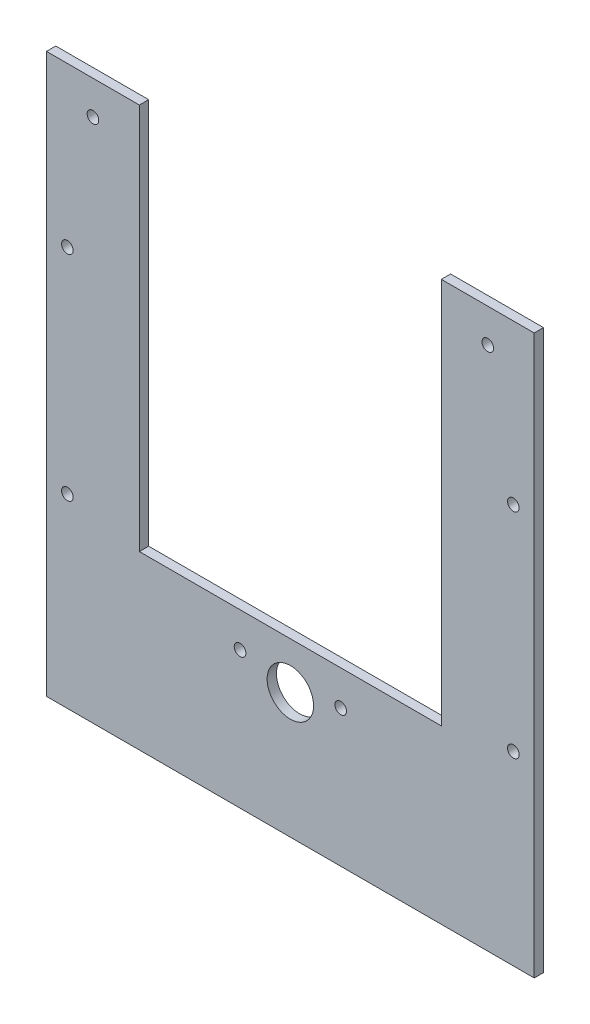
SolidWorks part; units mm, degrees
ref_plane "Alzado" through (0, 0, 0) normal (0, 0, 1) x (1, 0, 0)
ref_plane "Planta" through (0, 0, 0) normal (0, 1, 0) x (1, 0, 0)
ref_plane "Vista lateral" through (0, 0, 0) normal (1, 0, 0) x (0, 0, -1)
sketch "Croquis1" plane through (0, 0, 0) normal (0, 0, 1) x (1, 0, 0)
  line L0 (-79.4984, 944.1284) -> (-79.4984, 777.6284)
  line L1 (90.5016, 703.6284) -> (-119.4984, 703.6284)
  line L2 (90.5016, 703.6284) -> (90.5016, 944.1284)
  line L3 (90.5016, 944.1284) -> (50.5016, 944.1284)
  line L4 (-119.4984, 703.6284) -> (-119.4984, 944.1284)
  line L5 (-79.4984, 777.6284) -> (50.5016, 777.6284)
  line L6 (50.5016, 777.6284) -> (50.5016, 944.1284)
  line L7 (-79.4984, 944.1284) -> (-119.4984, 944.1284)
  circle A0 centre (70.5016, 929.6284) radius 2.5
  circle A1 centre (81.5016, 875.6184) radius 2.5
  circle A2 centre (81.5016, 783.6184) radius 2.5
  circle A3 centre (-36.1651, 762.6284) radius 2.5
  circle A4 centre (-110.4984, 783.6184) radius 2.5
  circle A5 centre (-110.4984, 875.6184) radius 2.5
  circle A6 centre (-99.4984, 929.6284) radius 2.5
  circle A7 centre (7.1683, 762.6284) radius 2.5
  circle A8 centre (-14.4984, 757.6284) radius 10
extrude "Saliente-Extruir1" add sketch "Croquis1" along normal blind 4
